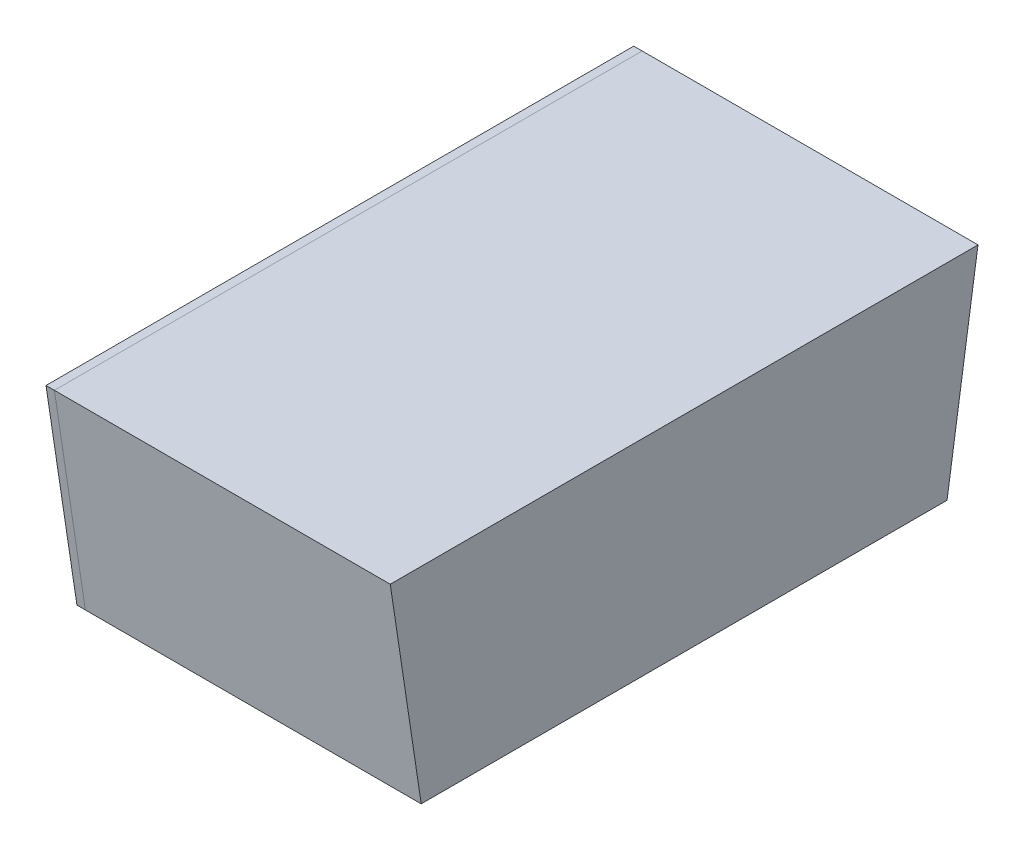
SolidWorks part; units mm, degrees
ref_plane "Front Plane" through (0, 0, 0) normal (0, 0, 1) x (1, 0, 0)
ref_plane "Top Plane" through (0, 0, 0) normal (0, 1, 0) x (1, 0, 0)
ref_plane "Right Plane" through (0, 0, 0) normal (1, 0, 0) x (0, 0, -1)
sketch "Sketch1" plane through (0, 0, 0) normal (1, 0, 0) x (0, 0, -1)
  line L0 (0, 161.91) -> (-23.4, 317.48)
  line L1 (-23.4, 317.48) -> (421.1, 317.48)
  line L2 (421.1, 317.48) -> (397.7, 161.91)
  line L3 (397.7, 161.91) -> (0, 161.91)
  point P4 (0, 0)
  point P5 (0, 0)
  dimension "D1" = 397.7
  dimension "D2" = 444.5
  dimension "D3" = 155.57
  dimension "D4" = 161.91
extrude "Boss-Extrude1" add sketch "Sketch1" along normal blind 254
sketch "Sketch5" plane through (0, 0, 0) normal (-1, 0, 0) x (0, 0, 1)
  line L4 (-397.7, 161.91) -> (0, 161.91)
  line L5 (0, 161.91) -> (23.4, 317.48)
  line L6 (23.4, 317.48) -> (-421.1, 317.48)
  line L7 (-421.1, 317.48) -> (-397.7, 161.91)
  line L8 (-397.7, 161.91) -> (0, 161.91)
  line L9 (0, 161.91) -> (23.4, 317.48)
  line L10 (23.4, 317.48) -> (-421.1, 317.48)
  line L11 (-421.1, 317.48) -> (-397.7, 161.91)
  dimension "D1" = 0
extrude "Boss-Extrude2" add sketch "Sketch5" along normal blind 6.35 separate body
ref_point "Lower Front" parameters "D1"=6.35
ref_point "Lower Back"
sketch3d "3DSketch2"
  line L0 (0, 317.48, 41.6562) -> (135.9379, 330.5306, 322.1192)
  line L1 (135.9379, 330.5306, 322.1192) -> (254, 317.48, 23.4)
  line L2 (-6.35, 161.91, 0) -> (132.085, 126.6694, 341.19)
  line L3 (132.085, 126.6694, 341.19) -> (247.65, 161.91, 0)
  line L4 (135.9379, 330.5306, 322.1192) -> (132.085, 126.6694, 341.19)
  line L5 (134.0114, 0, 331.6546) -> (134.0114, 457.2, 331.6546)
  line L6 (0, 317.48, 23.4) -> (0, 317.48, 41.6562)
  point P13 (134.0114, 228.6, 331.6546)
  point P15 (0, 0, 0)
  point P16 (0, 0, 0)
  dimension "D6" = 457.2
  dimension "D7" = 18.2562
  dimension "D1" = 369.8875
  dimension "D2" = 361.95
  dimension "D3" = 321.4687
  dimension "D4" = 311.9437
  dimension "D5" = 204.7875
sketch "Sketch2" plane through (254, 0, 0) normal (1, 0, 0) x (0, 0, -1)
  line L0 (-331.6546, 0) -> (-331.6546, 457.2) construction
  line L1 (-322.1192, 330.5306) -> (-341.19, 126.6694) construction
  line L2 (-331.6546, 0) -> (-331.6546, 457.2)
  line L3 (-322.1192, 330.5306) -> (-341.19, 126.6694)
  dimension "D1" = 5.344
ref_plane "Plane1" through (0, 0, 331.6546) normal (0, 0, 1) x (1, 0, 0)
sketch "Sketch3" plane through (0, 0, 331.6546) normal (0, 0, 1) x (1, 0, 0)
  line L0 (134.0114, 0) -> (134.0114, 457.2) construction
  line L1 (135.9379, 330.5306) -> (132.085, 126.6694) construction
  line L2 (134.0114, 0) -> (134.0114, 457.2)
  line L3 (135.9379, 330.5306) -> (132.085, 126.6694)
  dimension "D1" = 358.917
sketch3d "3DSketch3"
  line L0 (254, 317.48, -421.1) -> (124.6606, 320.0271, -712.9682)
  line L1 (124.6606, 320.0271, -712.9682) -> (0, 317.48, -427.45)
  line L2 (124.6606, 320.0271, -712.9682) -> (135.3378, 116.2939, -712.9682)
  line L3 (0, 317.48, -421.1) -> (0, 317.48, -427.45)
  line L4 (124.6606, 320.0271, -712.9682) -> (124.6606, 161.91, -712.9682) construction
  line L5 (124.6606, 320.0271, -712.9682) -> (124.6606, 317.48, -421.1) construction
  line L6 (0, 317.48, -427.45) -> (143.439, 319.9489, -704.012)
  line L9 (254, 317.48, -421.1) -> (0, 317.48, -421.1) construction
  line L10 (124.6606, 317.48, -421.1) -> (124.6606, 317.48, 23.4)
  line L11 (254, 317.48, 23.4) -> (0, 317.48, 23.4) construction
  line L15 (143.439, 319.9489, -704.012) -> (143.439, 317.48, -421.1)
  line L16 (143.439, 317.48, -421.1) -> (143.439, 317.48, 23.4)
  line L20 (143.439, 319.9489, -704.012) -> (135.3378, 116.2939, -712.9682)
  point P10 (144.0143, 319.9119, -703.7132)
  point P13 (146.3167, 319.742, -702.5022)
  point P16 (144.1778, 319.901, -703.628)
  point P18 (135.3378, 319.901, -703.628)
  point P20 (144.1778, 319.901, -703.628)
  point P21 (144.0143, 319.9119, -703.7132)
  point P22 (144.0143, 319.9119, -703.7132)
  point P23 (144.0143, 319.9119, -703.7132)
  point P25 (144.0143, 319.9119, -703.7132)
  point P26 (133.5401, 319.9918, -708.9249)
  point P27 (146.9353, 319.9329, -702.1706)
  dimension "D1" = 311.5564
  dimension "D2" = 319.2526
  dimension "D3" = 6.35
  dimension "D4" = 204.0128
  dimension "D5" = 3
  dimension "D6" = 0.5
  dimension "D7" = 0.5
  dimension "D8" = 204.0128
sketch3d "3DSketch5"
  line L0 (254, 317.48, -421.1) -> (117.4432, 319.9982, -709.6622)
  line L1 (117.4432, 319.9982, -709.6622) -> (0, 317.48, -421.1)
  line L2 (117.4432, 319.9982, -709.6622) -> (117.4432, 317.48, -421.1)
  line L3 (254, 317.48, -421.1) -> (0, 317.48, -421.1) construction
  line L4 (117.4432, 317.48, -421.1) -> (117.4432, 317.48, 23.4)
  line L5 (254, 317.48, 23.4) -> (0, 317.48, 23.4) construction
  line L6 (117.4432, 319.9982, -709.6622) -> (117.4432, 161.91, -709.6622) construction
  line L7 (117.4432, 319.9982, -709.6622) -> (117.4432, 117.069, -718.1674) construction
  line L8 (117.4432, 117.069, -718.1674) -> (136.6425, 117.069, -718.1674) construction
  line L10 (117.4432, 319.9982, -709.6622) -> (136.6425, 117.069, -718.1674)
  line L11 (136.6425, 320.4014, -706.6193) -> (136.6425, 161.91, -706.6193) construction
  line L12 (136.6425, 161.91, -706.6193) -> (136.6425, 117.069, -718.1674) construction
  line L14 (136.6425, 320.4014, -706.6193) -> (124.6499, 320.4014, -706.6193)
  line L15 (124.6499, 320.4014, -706.6193) -> (136.6425, 117.069, -718.1674)
  line L16 (136.6425, 117.069, -718.1674) -> (136.6425, 320.4014, -706.6193) construction
  line L17 (124.6499, 320.4014, -706.6193) -> (254, 317.48, -421.1)
  line L18 (124.6499, 320.4014, -706.6193) -> (0, 317.48, -421.1)
  dimension "D1" = 0.5
  dimension "D2" = 311.5564
  dimension "D3" = 319.2526
  dimension "D4" = 2.4
  dimension "D5" = 204.0128
  dimension "D6" = 5.4
  dimension "D7" = 204.0128
  dimension "D8" = 3.37
  dimension "D9" = 313.4665
